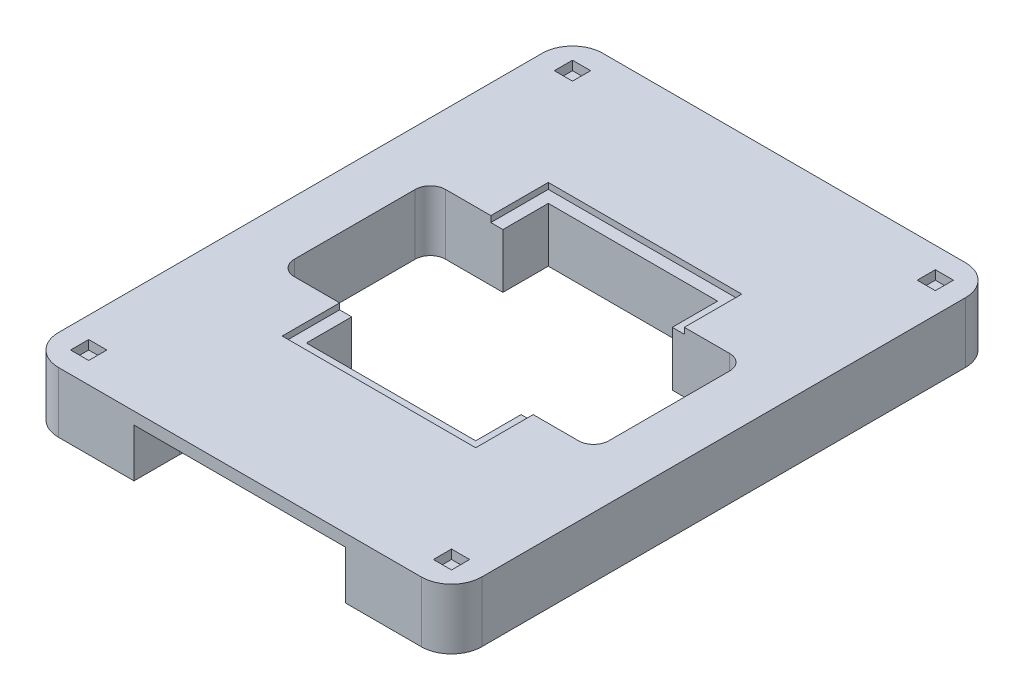
SolidWorks part; units mm, degrees
ref_plane "前视基准面" through (0, 0, 0) normal (0, 0, 1) x (1, 0, 0)
ref_plane "上视基准面" through (0, 0, 0) normal (0, 1, 0) x (1, 0, 0)
ref_plane "右视基准面" through (0, 0, 0) normal (1, 0, 0) x (0, 0, -1)
sketch "草图1" plane through (0, 0, 0) normal (0, 1, 0) x (1, 0, 0)
  line L1 (100, -100) -> (-100, -100)
  line L2 (100, -100) -> (100, 100)
  line L3 (100, 100) -> (-100, 100)
  line L4 (-100, -100) -> (-100, 100)
  line L5 (100, -100) -> (-100, 100) construction
  line L6 (100, 100) -> (-100, -100) construction
  point P1 (0, 0)
  dimension "D1" = 200
  dimension "D2" = 200
extrude "凸台-拉伸1" add sketch "草图1" along normal blind 20
sketch "草图2" plane through (0, 20, 0) normal (0, 1, 0) x (1, 0, 0)
  line L1 (70, -90) -> (-70, -90)
  line L2 (70, -90) -> (70, 90)
  line L3 (70, 90) -> (-70, 90)
  line L4 (-70, -90) -> (-70, 90)
  line L5 (70, -90) -> (-70, 90) construction
  line L6 (70, 90) -> (-70, -90) construction
  line L7 (100, -100) -> (-100, -100)
  line L8 (100, -100) -> (100, 100)
  line L9 (100, 100) -> (-100, 100)
  line L10 (-100, -100) -> (-100, 100)
  line L11 (100, -100) -> (-100, 100) construction
  line L12 (100, 100) -> (-100, -100) construction
  point P0 (0, 0)
  point P6 (0, 0)
  dimension "D1" = 140
  dimension "D2" = 180
extrude "切除-拉伸2" cut sketch "草图2" against normal through all
fillet "圆角1" radius 10 1 edges at (-70, 10, -90)
fillet "圆角2" radius 10 1 edges at (70, 10, -90)
fillet "圆角3" radius 10 1 edges at (70, 10, 90)
fillet "圆角4" radius 10 1 edges at (-70, 10, 90)
sketch "草图4" plane through (0, 0, 0) normal (0, -1, 0) x (1, 0, 0)
  line L5 (-60, 90) -> (60, 90) construction
  line L82 (-70, -80) -> (-70, 80) construction
  line L83 (-59.5, 84.9749) -> (-59.5, 86)
  line L95 (-59.5, 74) -> (-60.5, 74)
  line L97 (-59.5, 74) -> (-59.5, 75.0251)
  line L102 (-59.5, 86) -> (-60.5, 86)
  line L103 (-60.5, 74) -> (-60.5, 75.0251)
  line L108 (-66, 79.5) -> (-64.9749, 79.5)
  line L109 (-66, 79.5) -> (-66, 80.5)
  line L110 (-66, 80.5) -> (-64.9749, 80.5)
  line L111 (-54, 79.5) -> (-54, 80.5)
  line L115 (-60.5, 84.9749) -> (-60.5, 86)
  line L116 (-55.0251, 80.5) -> (-54, 80.5)
  line L120 (-55.0251, 79.5) -> (-54, 79.5)
  arc A5 (-60.5, 84.9749) -> (-64.9749, 80.5) centre (-60, 80) ccw
  arc A6 (-55.0251, 80.5) -> (-59.5, 84.9749) centre (-60, 80) ccw
  arc A7 (-59.5, 75.0251) -> (-55.0251, 79.5) centre (-60, 80) ccw
  arc A8 (-64.9749, 79.5) -> (-60.5, 75.0251) centre (-60, 80) ccw
  point P0 (0, 0)
  point P2 (-60, 80)
  dimension "D3" = 1
  dimension "D4" = 12
  dimension "D1" = 10
  dimension "D2" = 10
  dimension "D5" = 1
  dimension "D6" = 12
extrude "切除-拉伸4" cut sketch "草图4" against normal blind 5
mirror "镜向3" about plane through (0, 0, 0) normal (1, 0, 0) of "切除-拉伸4" second plane through (0, 0, 0) second plane normal (0, 0, 1)
sketch "草图5" plane through (0, 0, 0) normal (0, -1, 0) x (1, 0, 0)
  line L1 (60, -80) -> (-60, -80) construction
  line L2 (60, -80) -> (60, 80) construction
  line L3 (60, 80) -> (-60, 80) construction
  line L4 (-60, -80) -> (-60, 80) construction
  line L5 (60, -80) -> (-60, 80) construction
  line L6 (60, 80) -> (-60, -80) construction
  circle A0 centre (-60, 80) radius 5
  point P0 (0, 0)
  dimension "D3" = 10
  dimension "D1" = 120
  dimension "D2" = 160
extrude "切除-拉伸5" cut sketch "草图5" against normal blind 6.2
sketch "草图7" plane through (0, 0, 0) normal (0, -1, 0) x (1, 0, 0)
  line L0 (-60, 90) -> (60, 90) construction
  line L1 (35, 110) -> (-35, 110)
  line L2 (35, 110) -> (35, 75)
  line L3 (30, 70) -> (-30, 70)
  line L4 (-35, 110) -> (-35, 75)
  line L5 (35, 110) -> (-35, 70) construction
  line L6 (35, 70) -> (-35, 110) construction
  arc A0 (-30, 70) -> (-35, 75) centre (-30, 75) cw
  arc A1 (30, 70) -> (35, 75) centre (30, 75) ccw
  point P0 (0, 90)
  dimension "D3" = 5
  dimension "D4" = 5
  dimension "D1" = 70
  dimension "D2" = 40
extrude "切除-拉伸7" cut sketch "草图7" against normal blind 16
mirror "镜向6" about plane through (0, 0, 0) normal (0, 0, 1) of "切除-拉伸7"
sketch "草图8" plane through (0, 0, 0) normal (0, -1, 0) x (1, 0, 0)
  line L5 (40.5, -40.5) -> (-40.5, -40.5) construction
  line L6 (40.5, -40.5) -> (40.5, 40.5) construction
  line L7 (40.5, 40.5) -> (-40.5, 40.5) construction
  line L8 (-40.5, -40.5) -> (-40.5, 40.5) construction
  line L9 (40.5, -40.5) -> (-40.5, 40.5) construction
  line L10 (40.5, 40.5) -> (-40.5, -40.5) construction
  circle A4 centre (-40.5, 40.5) radius 4.1
  point P0 (0, 0)
  dimension "D1" = 81
  dimension "D2" = 81
extrude "切除-拉伸8" cut sketch "草图8" against normal blind 4
draft "拔模2" type of draft neutral plane draft angle 10 faces to draft 1 face at (-40.5, 4, 36.4) neutral plane through (-40.5, 4, 40.5) neutral plane normal (0, -1, 0) parameters "D1"=10
mirror "镜向10" about plane through (0, 0, 0) normal (1, 0, 0) of "拔模2", "切除-拉伸8"
mirror "镜向11" about plane through (0, 0, 0) normal (0, 0, 1) of "切除-拉伸8", "拔模2"
sketch "草图14" plane through (0, 20, 0) normal (0, 1, 0) x (1, 0, 0)
  line L1 (60, -80) -> (-60, -80) construction
  line L2 (60, -80) -> (60, 80) construction
  line L3 (60, 80) -> (-60, 80) construction
  line L4 (-60, -80) -> (-60, 80) construction
  line L5 (60, -80) -> (-60, 80) construction
  line L6 (60, 80) -> (-60, -80) construction
  line L7 (-57, 77) -> (-63, 77)
  line L8 (-57, 77) -> (-57, 83)
  line L9 (-57, 83) -> (-63, 83)
  line L10 (-63, 77) -> (-63, 83)
  line L11 (-57, 77) -> (-63, 83) construction
  line L12 (-57, 83) -> (-63, 77) construction
  point P0 (0, 0)
  dimension "D1" = 120
  dimension "D2" = 160
  dimension "D3" = 6
  dimension "D4" = 6
extrude "切除-拉伸9" cut sketch "草图14" against normal blind 3
mirror "镜向12" about plane through (0, 0, 0) normal (1, 0, 0) of "切除-拉伸9" second plane through (0, 0, 0) second plane normal (0, 0, 1)
sketch "草图15" plane through (0, 20, 0) normal (0, 1, 0) x (1, 0, 0)
  line L1 (32, -44) -> (-32, -44)
  line L2 (32, -44) -> (32, 44)
  line L3 (32, 44) -> (-32, 44)
  line L4 (-32, -44) -> (-32, 44)
  line L5 (32, -44) -> (-32, 44) construction
  line L6 (32, 44) -> (-32, -44) construction
  point P0 (0, 0)
  dimension "D1" = 88
  dimension "D2" = 64
extrude "切除-拉伸10" cut sketch "草图15" against normal blind 2
sketch "草图16" plane through (0, 18, 0) normal (0, 1, 0) x (1, 0, 0)
  line L1 (28, -40) -> (-28, -40)
  line L2 (28, -40) -> (28, 40)
  line L3 (28, 40) -> (-28, 40)
  line L4 (-28, -40) -> (-28, 40)
  line L5 (28, -40) -> (-28, 40) construction
  line L6 (28, 40) -> (-28, -40) construction
  point P0 (0, 0)
  dimension "D1" = 56
  dimension "D2" = 80
extrude "切除-拉伸11" cut sketch "草图16" against normal through all
sketch "草图17" plane through (0, 20, 0) normal (0, 1, 0) x (1, 0, 0)
  line L1 (47, -25) -> (-47, -25)
  line L2 (52, -20) -> (52, 20)
  line L3 (47, 25) -> (-47, 25)
  line L4 (-52, -20) -> (-52, 20)
  line L5 (52, -25) -> (-52, 25) construction
  line L6 (52, 25) -> (-52, -25) construction
  arc A0 (47, -25) -> (52, -20) centre (47, -20) ccw
  arc A1 (52, 20) -> (47, 25) centre (47, 20) ccw
  arc A2 (-47, -25) -> (-52, -20) centre (-47, -20) cw
  arc A3 (-52, 20) -> (-47, 25) centre (-47, 20) cw
  point P0 (0, 0)
  dimension "D3" = 5
  dimension "D1" = 104
  dimension "D2" = 50
extrude "切除-拉伸12" cut sketch "草图17" against normal through all
